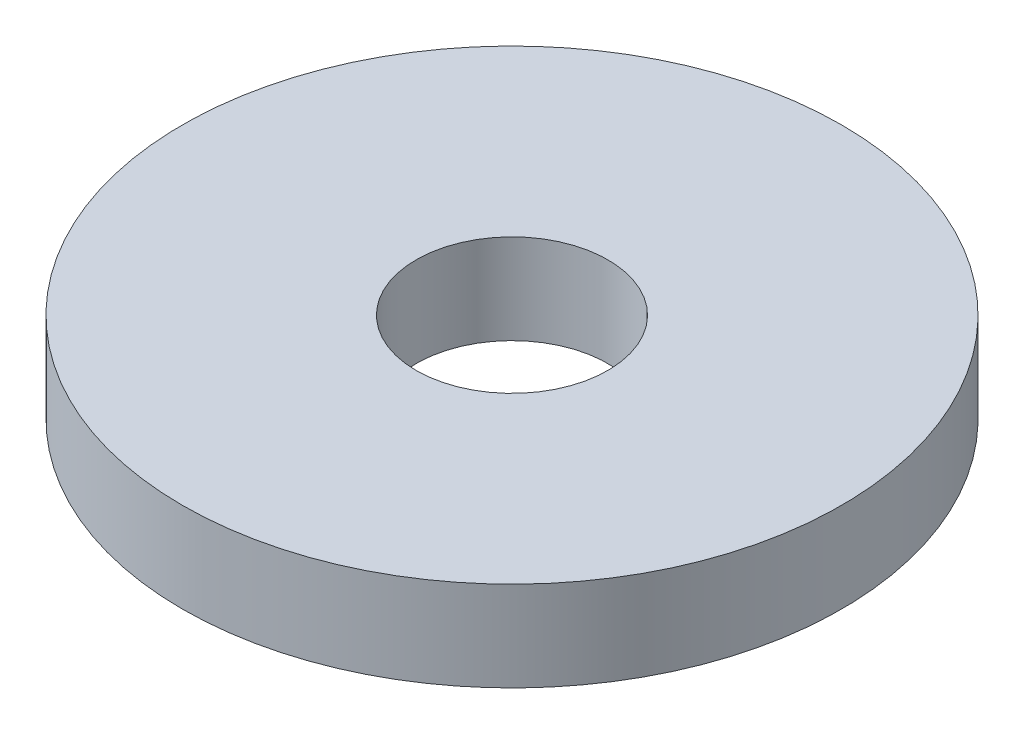
SolidWorks part; units mm, degrees
ref_plane "Front Plane" through (0, 0, 0) normal (0, 0, 1) x (1, 0, 0)
ref_plane "Top Plane" through (0, 0, 0) normal (0, 1, 0) x (1, 0, 0)
ref_plane "Right Plane" through (0, 0, 0) normal (1, 0, 0) x (0, 0, -1)
sketch "Sketch1" plane through (0, 0, 0) normal (0, 1, 0) x (1, 0, 0)
  circle A0 centre (0, 0) radius 5.5
  circle A1 centre (0, 0) radius 1.6
  dimension "D1" = 11
  dimension "D2" = 3.2
extrude "Boss-Extrude1" add sketch "Sketch1" along normal blind 1.5
